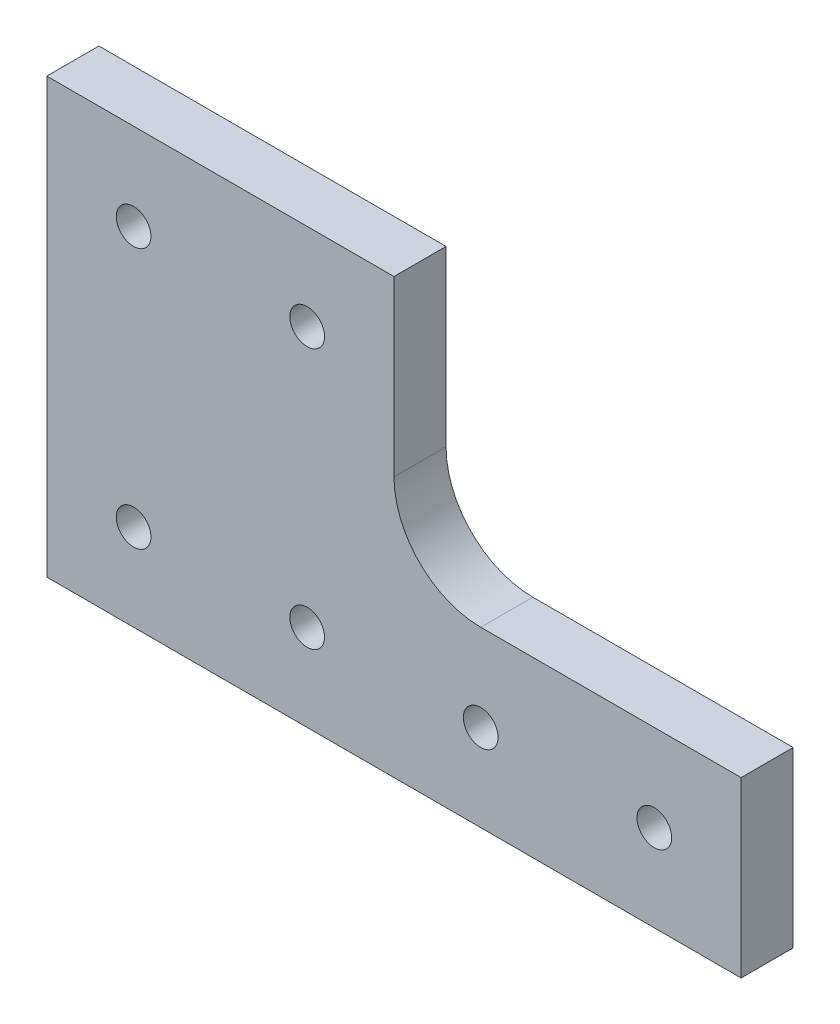
SolidWorks part; units mm, degrees
ref_plane "Plano frontal" through (0, 0, 0) normal (0, 0, 1) x (1, 0, 0)
ref_plane "Plano superior" through (0, 0, 0) normal (0, 1, 0) x (1, 0, 0)
ref_plane "Plano direito" through (0, 0, 0) normal (1, 0, 0) x (0, 0, -1)
sketch "Esboço1" plane through (0, 0, 0) normal (0, 0, 1) x (1, 0, 0)
  line L0 (10, 0) -> (10, 50) construction
  line L1 (0, 0) -> (40, 0)
  line L2 (0, 0) -> (0, 50)
  line L3 (0, 50) -> (40, 50)
  line L4 (40, 0) -> (40, 50)
  line L5 (40, 0) -> (80, 0)
  line L6 (40, 0) -> (40, 20)
  line L7 (40, 20) -> (80, 20)
  line L8 (80, 0) -> (80, 20)
  line L9 (30, 0) -> (30, 50) construction
  line L10 (0, 10) -> (40, 10) construction
  line L11 (0, 40) -> (40, 40) construction
  line L12 (50, 0) -> (50, 50) construction
  line L13 (70, 0) -> (70, 20) construction
  line L14 (80, 10) -> (40, 10) construction
  circle A0 centre (10, 40) radius 2
  circle A1 centre (30, 40) radius 2
  circle A2 centre (10, 10) radius 2
  circle A3 centre (30, 10) radius 2
  circle A4 centre (50, 10) radius 2
  circle A5 centre (70, 10) radius 2
  dimension "D11" = 4
  dimension "D1" = 40
  dimension "D2" = 50
  dimension "D3" = 20
  dimension "D4" = 40
  dimension "D5" = 10
  dimension "D6" = 10
  dimension "D7" = 10
  dimension "D8" = 10
  dimension "D9" = 10
  dimension "D10" = 10
extrude "Ressalto-extrusão1" add sketch "Esboço1" along normal blind 6 contours L1 L4 L3 L2 A3 A2 A1 A0 | L5 L8 L7 L4 A5 A4
fillet "Filete1" radius 10 1 edges at (40, 20, 3)
